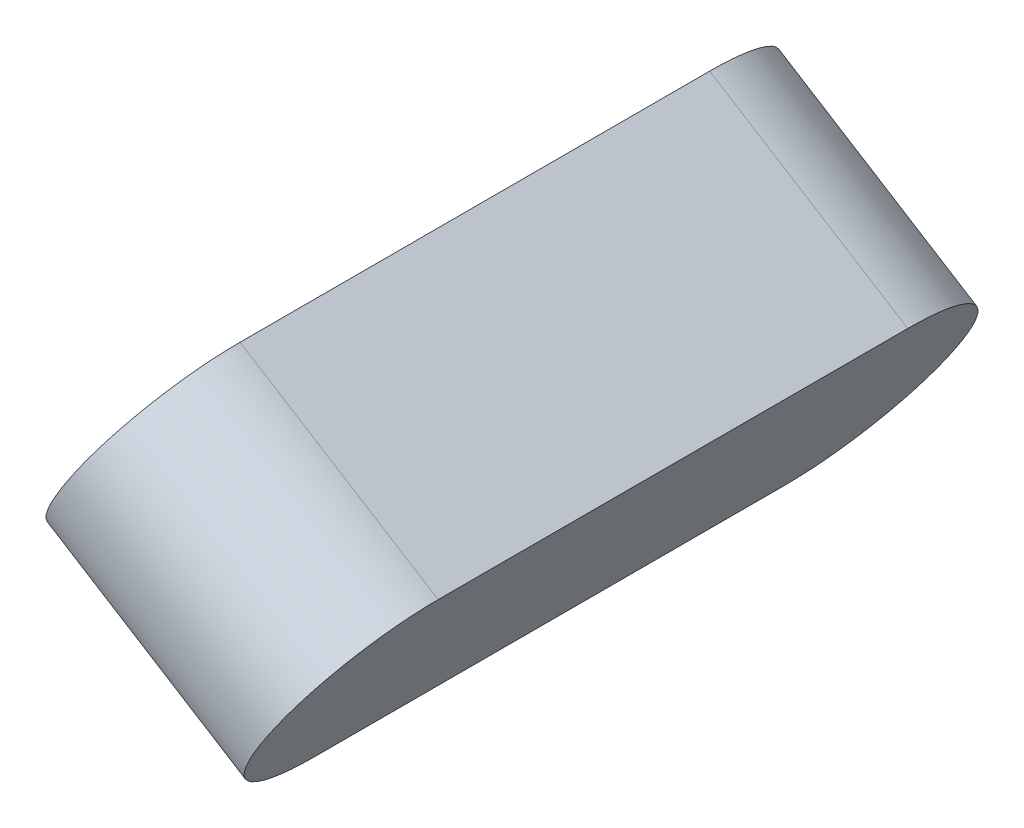
SolidWorks part; units mm, degrees
ref_plane "Plan de face" through (0, 0, 0) normal (0, 0, 1) x (1, 0, 0)
ref_plane "Plan de dessus" through (0, 0, 0) normal (0, 1, 0) x (1, 0, 0)
ref_plane "Plan de droite" through (0, 0, 0) normal (1, 0, 0) x (0, 0, -1)
sketch "Esquisse1" plane through (-30.7986, 19.2491, 0) normal (-0.848, 0.53, 0) x (0, 0, 1)
  line L0 (-155, 1.5239) -> (-155, -18.4761)
  line L1 (-155, 1.5239) -> (-114.7986, 1.5239)
  line L2 (-155, -18.4761) -> (-114.7986, -18.4761)
  line L3 (-114.7986, 1.5239) -> (-114.7986, -18.4761)
  circle A0 centre (-155, -8.4761) radius 10
  circle A1 centre (-114.7986, -8.4761) radius 10
extrude "Boss.-Extru.1" add sketch "Esquisse1" against normal blind 20 from offset 35 contours L0 A0 | L0 A0 | A1 L1 A0 L2 | L3 A1 | L3 A1
